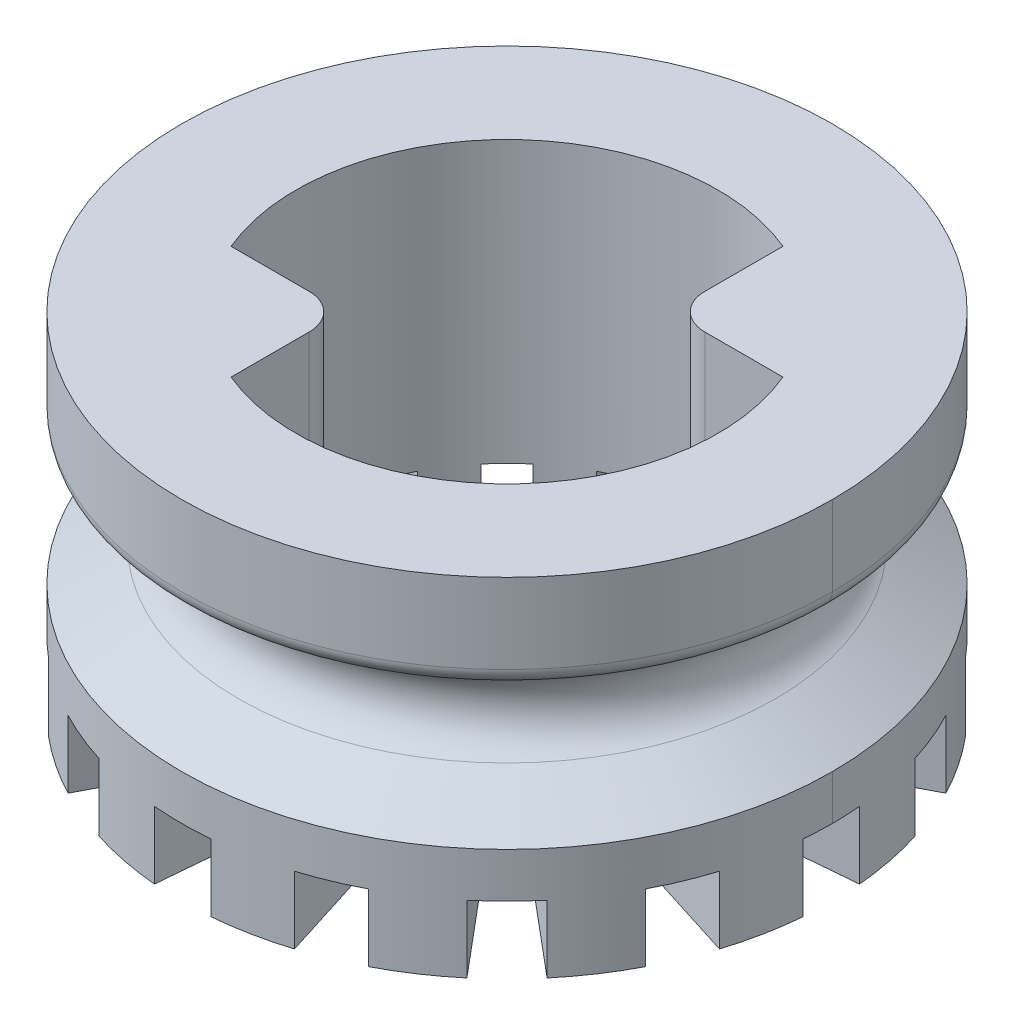
SolidWorks part; units mm, degrees
material "PW40:29:C1:0:1:2:Sc:3:Re:17:"
ref_plane "Front" through (0, 0, 0) normal (0, 0, 1) x (1, 0, 0)
ref_plane "Top" through (0, 0, 0) normal (0, 1, 0) x (1, 0, 0)
ref_plane "Right" through (0, 0, 0) normal (1, 0, 0) x (0, 0, -1)
sketch "Sketch1" plane through (0, 0, 0) normal (0, 1, 0) x (1, 0, 0)
  circle A0 centre (0, 0) radius 3.683
  dimension "D1" = 7.366
extrude "Base-Extrude" add sketch "Sketch1" along normal blind 3.937
sketch "Sketch2" plane through (0, 3.937, 0) normal (0, 1, 0) x (-1, 0, 0)
  circle A0 centre (0, 0) radius 2.3876
  dimension "D1" = 4.7752
extrude "Cut-Extrude1" cut sketch "Sketch2" against normal through all
split line "Split Line1"
sketch "Sketch4" plane through (0, 0, 0) normal (0, 0, 1) x (1, 0, 0)
  line L0 (-0.8167, 2.0955) -> (6.9225, 2.0955) construction
  line L1 (3.683, 2.921) -> (3.0384, 2.5298)
  line L2 (3.683, 0) -> (3.683, 3.937) construction
  line L3 (-3.683, 3.937) -> (3.683, 3.937) construction
  line L4 (3.683, 1.27) -> (3.0384, 1.6612)
  line L5 (0, 0) -> (0, 4.7179) construction
  line L6 (3.683, 2.921) -> (3.683, 1.27)
  arc A0 (3.0384, 2.5298) -> (3.0384, 1.6612) centre (3.302, 2.0955) ccw
  dimension "D4" = 0.508
  dimension "D1" = 1.016
  dimension "D2" = 1.651
  dimension "D3" = 5.588
revolve "Cut-Revolve1" cut sketch "Sketch4" angle 360 about L5
sketch "Sketch5" plane through (16.4943, 0, 2.5829) normal (0, -1, 0) x (1, 0, 0)
  line L0 (-16.4943, -2.5829) -> (-23.5814, -2.5829) construction
  line L1 (-16.4943, -2.5829) -> (-27.4899, -1.6209) construction
  line L2 (-18.8728, -2.3748) -> (-20.1633, -2.2619)
  line L3 (-18.8728, -2.791) -> (-20.1633, -2.9039)
  circle A0 centre (-16.4943, -2.5829) radius 2.3876 construction
  arc A1 (-18.8728, -2.3748) -> (-18.8728, -2.791) centre (-16.4943, -2.5829) ccw
  arc A2 (-20.1773, -2.5829) -> (-12.8113, -2.5829) centre (-16.4943, -2.5829) ccw construction
  arc A3 (-20.1633, -2.2619) -> (-20.1633, -2.9039) centre (-16.4943, -2.5829) ccw
  dimension "D1" = 10
extrude "Cut-Extrude2" cut sketch "Sketch5" against normal blind 0.762
pattern_circular "CirPattern1" count 16 every 22.5 about axis through (0, 0, 0) along (0, 1, 0) of "Cut-Extrude2"
sketch "Sketch6" plane through (0, 3.937, 0) normal (0, 1, 0) x (-1, 0, 0)
  line L0 (0, 0) -> (-4.1536, 0) construction
  line L1 (0, 0) -> (0, -5.1565) construction
  line L2 (-0.9208, -2.2029) -> (-0.9207, -0.9208)
  line L3 (-0.9207, -0.9208) -> (-2.2029, -0.9208)
  line L4 (0, 0) -> (-3.0791, 3.0791) construction
  line L5 (2.2029, 0.9207) -> (0.9208, 0.9207)
  line L6 (0.9208, 0.9207) -> (0.9208, 2.2029)
  circle A0 centre (0, 0) radius 2.3876 construction
  arc A1 (-2.2029, -0.9208) -> (-0.9208, -2.2029) centre (0, 0) ccw
  arc A2 (2.2029, 0.9207) -> (0.9208, 2.2029) centre (0, 0) ccw
  dimension "D1" = 0.9207
  dimension "D2" = 45
extrude "Boss-Extrude1" add sketch "Sketch6" against normal up to surface (3.175 mm away)
fillet "Fillet1" radius 0.3969 2 edges at (-0.9208, 2.3495, 0.9207) (0.9207, 2.3495, -0.9208)
fillet "Fillet2" radius 0.1984 2 edges at (0, 2.921, 3.683) (0, 2.921, -3.683)
